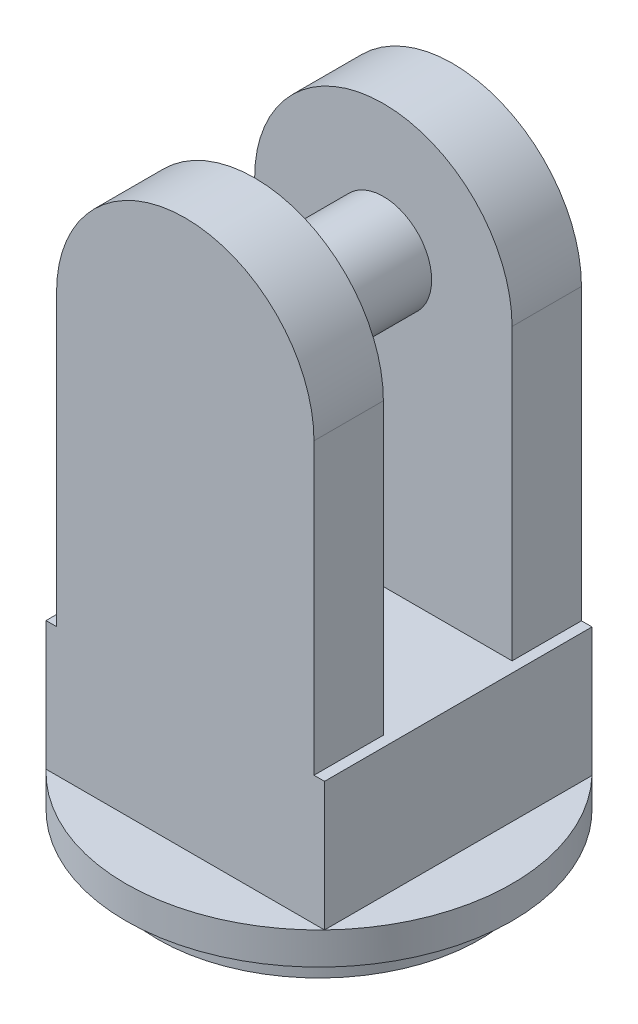
SolidWorks part; units mm, degrees
ref_plane "Front Plane" through (0, 0, 0) normal (0, 0, 1) x (1, 0, 0)
ref_plane "Top Plane" through (0, 0, 0) normal (0, 1, 0) x (1, 0, 0)
ref_plane "Right Plane" through (0, 0, 0) normal (1, 0, 0) x (0, 0, -1)
sketch "Sketch1" plane through (0, 0, 0) normal (0, 1, 0) x (1, 0, 0)
  circle A0 centre (0, 0) radius 50
  dimension "D1" = 100
extrude "Boss-Extrude1" add sketch "Sketch1" along normal blind 10
sketch "Sketch2" plane through (0, 10, 0) normal (0, 1, 0) x (1, 0, 0)
  circle A0 centre (0, 0) radius 15
extrude "Cut-Extrude1" cut sketch "Sketch2" against normal blind 10
sketch "Sketch3" plane through (0, 10, 0) normal (0, 1, 0) x (1, 0, 0)
  circle A0 centre (0, 0) radius 60
extrude "Boss-Extrude2" add sketch "Sketch3" along normal blind 10
sketch "Sketch4" plane through (0, 20, 0) normal (0, 1, 0) x (1, 0, 0)
  line L1 (-43.2733, 41.5622) -> (43.2733, 41.5622)
  line L2 (-43.2733, 41.5622) -> (-43.2733, -41.5622)
  line L3 (-43.2733, -41.5622) -> (43.2733, -41.5622)
  line L4 (43.2733, 41.5622) -> (43.2733, -41.5622)
  line L5 (-43.2733, 41.5622) -> (43.2733, -41.5622) construction
  line L6 (-43.2733, -41.5622) -> (43.2733, 41.5622) construction
  circle A0 centre (0, 0) radius 60 construction
  point P0 (0, 0)
extrude "Boss-Extrude3" add sketch "Sketch4" along normal blind 40
sketch "Sketch15" plane through (0, 0, 41.5622) normal (0, 0, 1) x (1, 0, 0)
  line L0 (0, 60) -> (0, 150) construction
  line L1 (-43.2733, 60) -> (43.2733, 60) construction
  line L2 (-40, 60) -> (-40, 150)
  line L3 (40, 60) -> (40, 150)
  line L4 (-50, 0) -> (50, 0) construction
  arc A0 (-40, 60) -> (40, 60) centre (0, 60) ccw
  arc A1 (40, 150) -> (-40, 150) centre (0, 150) ccw
  point P5 (0, 105)
  dimension "D1" = 150
  dimension "D2" = 80
extrude "Boss-Extrude9" add sketch "Sketch15" against normal up to surface (83.1245 mm away) up to face at (0, 40, -41.5622)
sketch "Sketch16" plane through (-40, 0, 0) normal (-1, 0, 0) x (0, 0, 1)
  line L0 (-41.5622, 150) -> (41.5622, 150) construction
  line L1 (-20, 240) -> (20, 240)
  line L2 (-20, 240) -> (-20, 60)
  line L3 (-20, 60) -> (20, 60)
  line L4 (20, 240) -> (20, 60)
  line L5 (-20, 240) -> (20, 60) construction
  line L6 (-20, 60) -> (20, 240) construction
  line L7 (-41.5622, 60) -> (41.5622, 60) construction
  point P0 (0, 150)
  dimension "D1" = 40
extrude "Cut-Extrude6" cut sketch "Sketch16" against normal blind 1000
sketch "Sketch17" plane through (0, 0, 41.5622) normal (0, 0, 1) x (1, 0, 0)
  circle A0 centre (0, 150) radius 15
extrude "Boss-Extrude10" add sketch "Sketch17" against normal up to surface (61.5622 mm away) up to face at (0, 115, -20)
